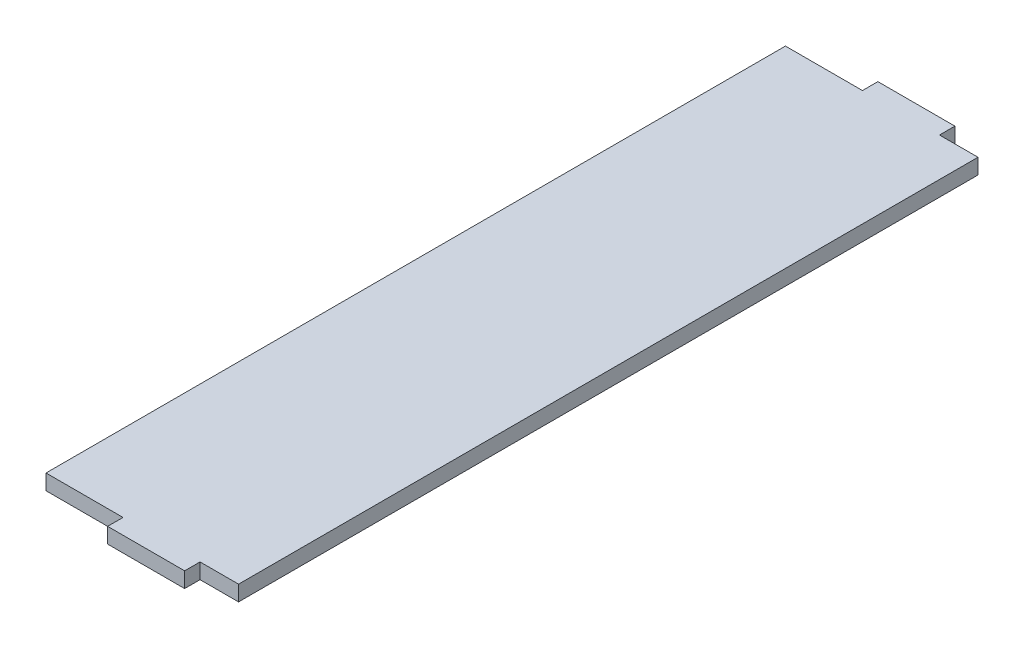
SolidWorks part; units mm, degrees
ref_plane "前视基准面" through (0, 0, 0) normal (0, 0, 1) x (1, 0, 0)
ref_plane "上视基准面" through (0, 0, 0) normal (0, 1, 0) x (1, 0, 0)
ref_plane "右视基准面" through (0, 0, 0) normal (1, 0, 0) x (0, 0, -1)
sketch "草图2" plane through (0, 0, 0) normal (0, 1, 0) x (1, 0, 0)
  line L0 (0, 0) -> (0, 288)
  line L1 (0, 288) -> (30, 288)
  line L2 (75, 288) -> (60, 288)
  line L3 (75, 0) -> (60, 0)
  line L4 (30, 0) -> (0, 0)
  line L5 (30, 294) -> (60, 294)
  line L6 (60, 294) -> (60, 288)
  line L8 (30, -6) -> (60, -6)
  line L9 (60, -6) -> (60, 0)
  line L10 (30, -6) -> (30, 0)
  line L11 (30, 294) -> (30, 288)
  line L13 (75, 288) -> (75, 0)
extrude "凸台-拉伸1" add sketch "草图2" along normal blind 6
